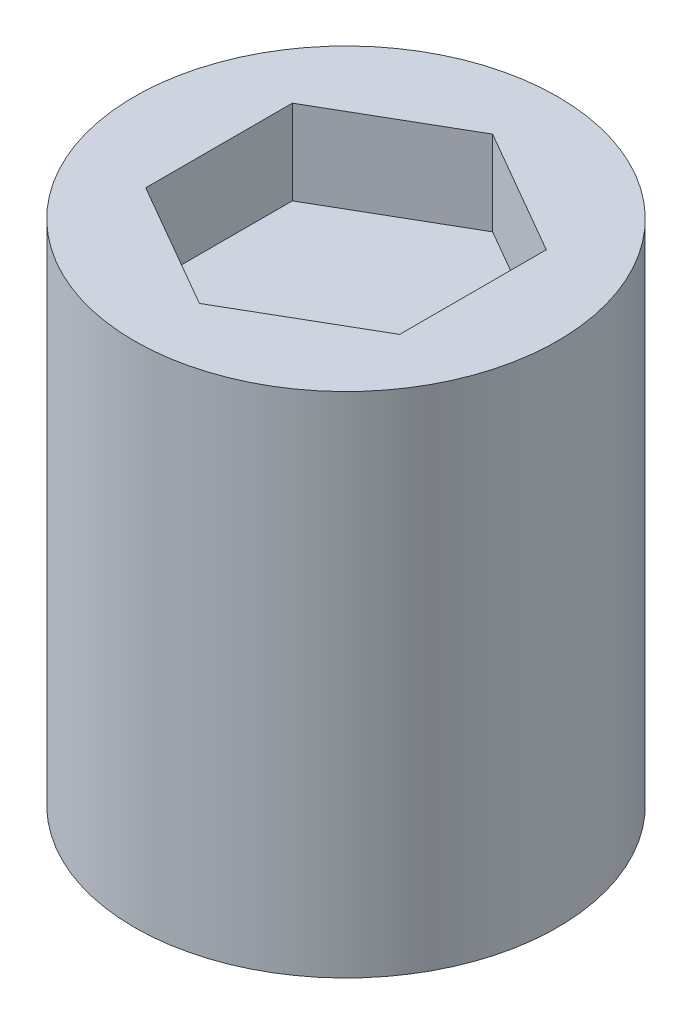
SolidWorks part; units mm, degrees
ref_plane "Front Plane" through (0, 0, 0) normal (0, 0, 1) x (1, 0, 0)
ref_plane "Top Plane" through (0, 0, 0) normal (0, 1, 0) x (1, 0, 0)
ref_plane "Right Plane" through (0, 0, 0) normal (1, 0, 0) x (0, 0, -1)
sketch "Sketch2" plane through (0, 0, 0) normal (0, 1, 0) x (1, 0, 0)
  circle A0 centre (0, 0) radius 12.5
  dimension "D1" = 25
extrude "Boss-Extrude1" add sketch "Sketch2" along normal blind 30
sketch "Sketch3" plane through (0, 0, 0) normal (0, -1, 0) x (-1, 0, 0)
  circle A0 centre (0, 0) radius 2.5
  dimension "D1" = 5
extrude "Cut-Extrude1" cut sketch "Sketch3" against normal blind 10
sketch "Sketch4" plane through (0, 10, 0) normal (0, -1, 0) x (1, 0, 0)
  line L0 (2, 1.5) -> (2, -1.5)
  circle A0 centre (0, 0) radius 2.5 construction
  arc A1 (2, 1.5) -> (2, -1.5) centre (0, 0) ccw
  dimension "D1" = 3
extrude "Cut-Extrude2" cut sketch "Sketch4" against normal blind 10
sketch "Sketch5" plane through (0, 30, 0) normal (0, 1, 0) x (1, 0, 0)
  line L1 (0, 8.6603) -> (-7.5, 4.3301)
  line L2 (-7.5, 4.3301) -> (-7.5, -4.3301)
  line L3 (-7.5, -4.3301) -> (0, -8.6603)
  line L4 (0, -8.6603) -> (7.5, -4.3301)
  line L5 (7.5, -4.3301) -> (7.5, 4.3301)
  line L6 (7.5, 4.3301) -> (0, 8.6603)
  circle A0 centre (0, 0) radius 7.5 construction
  dimension "D1" = 15
extrude "Cut-Extrude3" cut sketch "Sketch5" against normal blind 5
